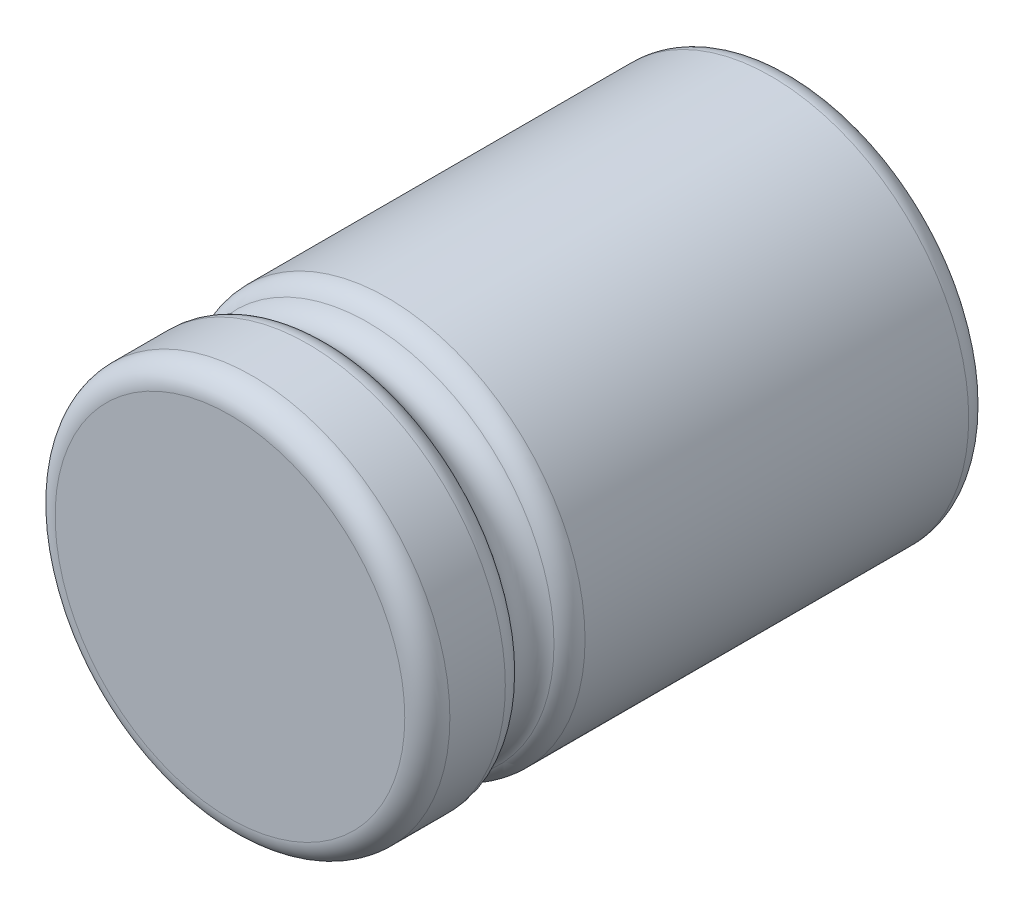
SolidWorks part; units mm, degrees
ref_plane "Front Plane" through (0, 0, 0) normal (0, 0, 1) x (1, 0, 0)
ref_plane "Top Plane" through (0, 0, 0) normal (0, 1, 0) x (1, 0, 0)
ref_plane "Right Plane" through (0, 0, 0) normal (1, 0, 0) x (0, 0, -1)
sketch "Sketch1" plane through (0, 0, 0) normal (0, 0, 1) x (1, 0, 0)
  circle A0 centre (0, 0) radius 17.5
  dimension "D1" = 35
extrude "Boss-Extrude1" add sketch "Sketch1" along normal blind 50
fillet "Fillet1" radius 2 2 edges at (17.5, 0, 50) (17.5, 0, 0)
sketch "Sketch2" plane through (0, 0, 0) normal (0, 1, 0) x (1, 0, 0)
  line L0 (17.5, -48) -> (17.5, -2) construction
  circle A0 centre (17.5, -39.5504) radius 2.0611
  point P4 (17.5, -39.5504)
sweep "Cut-Sweep1" cut profiles "Sketch2" path edge at (17.5, 0, 48)
fillet "Fillet2" radius 2 2 edges at (-17.5, 0, 41.6115) (17.5, 0, 37.4893)
